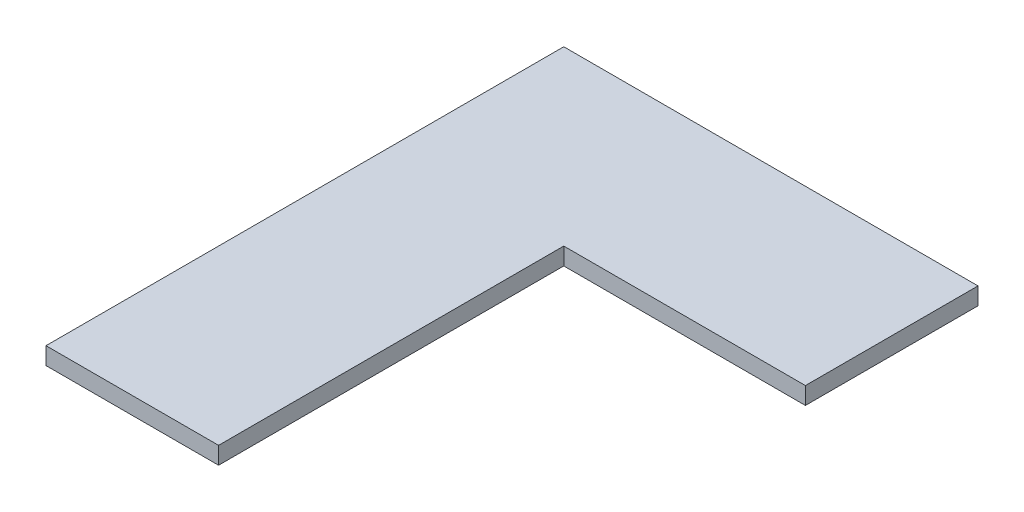
SolidWorks part; units mm, degrees
ref_plane "Front Plane" through (0, 0, 0) normal (0, 0, 1) x (1, 0, 0)
ref_plane "Top Plane" through (0, 0, 0) normal (0, 1, 0) x (1, 0, 0)
ref_plane "Right Plane" through (0, 0, 0) normal (1, 0, 0) x (0, 0, -1)
sketch "Sketch1" plane through (0, 0, 0) normal (0, 1, 0) x (1, 0, 0)
  line L0 (0, 0) -> (0, -30)
  line L1 (0, 0) -> (10, 0)
  line L2 (10, 0) -> (10, -30)
  line L3 (0, -30) -> (10, -30)
  line L4 (10, 0) -> (24, 0)
  line L5 (24, 0) -> (24, -10)
  line L6 (24, -10) -> (10, -10)
  dimension "D1" = 30
  dimension "D2" = 10
  dimension "D3" = 30
  dimension "D4" = 14
  dimension "D6" = 10
extrude "Boss-Extrude1" add sketch "Sketch1" along normal blind 1 contours L0 L3 L2 L1 | L6 L5 L4 L2
